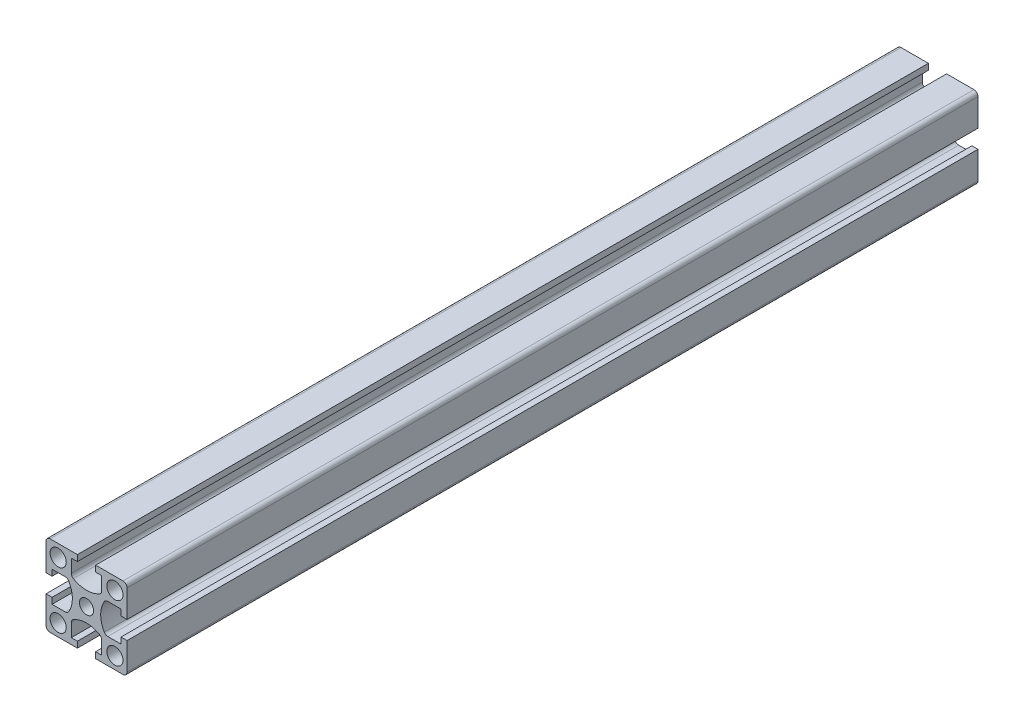
SolidWorks part; units mm, degrees
ref_plane "Front Plane" through (0, 0, 0) normal (0, 0, 1) x (1, 0, 0)
ref_plane "Top Plane" through (0, 0, 0) normal (0, 1, 0) x (1, 0, 0)
ref_plane "Right Plane" through (0, 0, 0) normal (1, 0, 0) x (0, 0, -1)
sketch "Sketch1" plane through (0, 0, 0) normal (0, 0, 1) x (1, 0, 0)
  line L64 (-20, 18) -> (-20, 4.5)
  line L65 (-20, 4.5) -> (-17, 4.5)
  line L66 (-17, 4.5) -> (-17, 7.5)
  line L67 (-17, 7.5) -> (-10.4737, 7.5)
  line L68 (-10.4737, -7.5) -> (-17, -7.5)
  line L69 (-17, -7.5) -> (-17, -4.5)
  line L70 (-17, -4.5) -> (-20, -4.5)
  line L71 (-20, -4.5) -> (-20, -18)
  line L72 (-18, -20) -> (-4.5, -20)
  line L73 (-4.5, -20) -> (-4.5, -17)
  line L74 (-4.5, -17) -> (-7.5, -17)
  line L75 (-7.5, -17) -> (-7.5, -10.4737)
  line L76 (7.5, -10.4737) -> (7.5, -17)
  line L77 (7.5, -17) -> (4.5, -17)
  line L78 (4.5, -17) -> (4.5, -20)
  line L79 (4.5, -20) -> (18, -20)
  line L80 (20, -18) -> (20, -4.5)
  line L81 (20, -4.5) -> (17, -4.5)
  line L82 (17, -4.5) -> (17, -7.5)
  line L83 (17, -7.5) -> (10.4737, -7.5)
  line L84 (10.4737, 7.5) -> (17, 7.5)
  line L85 (17, 7.5) -> (17, 4.5)
  line L86 (17, 4.5) -> (20, 4.5)
  line L87 (20, 4.5) -> (20, 18)
  line L88 (18, 20) -> (4.5, 20)
  line L89 (4.5, 20) -> (4.5, 17)
  line L90 (4.5, 17) -> (7.5, 17)
  line L91 (7.5, 17) -> (7.5, 10.4737)
  line L92 (-7.5, 10.4737) -> (-7.5, 17)
  line L93 (-7.5, 17) -> (-4.5, 17)
  line L94 (-4.5, 17) -> (-4.5, 20)
  line L95 (-4.5, 20) -> (-18, 20)
  circle A5 centre (-14, -14) radius 4
  circle A6 centre (14, -14) radius 4
  circle A7 centre (14, 14) radius 4
  circle A8 centre (0, 0) radius 3.5
  circle A9 centre (-14, 14) radius 4
  arc A32 (-18, 20) -> (-20, 18) centre (-18, 18) ccw
  arc A33 (-8.7417, 6.5) -> (-10.4737, 7.5) centre (-10.4737, 5.5) ccw
  arc A34 (-8.7417, -6.5) -> (-8.7417, 6.5) centre (-20, 0) ccw
  arc A35 (-10.4737, -7.5) -> (-8.7417, -6.5) centre (-10.4737, -5.5) ccw
  arc A36 (-20, -18) -> (-18, -20) centre (-18, -18) ccw
  arc A37 (-6.5, -8.7417) -> (-7.5, -10.4737) centre (-5.5, -10.4737) ccw
  arc A38 (6.5, -8.7417) -> (-6.5, -8.7417) centre (0, -20) ccw
  arc A39 (7.5, -10.4737) -> (6.5, -8.7417) centre (5.5, -10.4737) ccw
  arc A40 (18, -20) -> (20, -18) centre (18, -18) ccw
  arc A41 (8.7417, -6.5) -> (10.4737, -7.5) centre (10.4737, -5.5) ccw
  arc A42 (8.7417, 6.5) -> (8.7417, -6.5) centre (20, 0) ccw
  arc A43 (10.4737, 7.5) -> (8.7417, 6.5) centre (10.4737, 5.5) ccw
  arc A44 (20, 18) -> (18, 20) centre (18, 18) ccw
  arc A45 (6.5, 8.7417) -> (7.5, 10.4737) centre (5.5, 10.4737) ccw
  arc A46 (-6.5, 8.7417) -> (6.5, 8.7417) centre (0, 20) ccw
  arc A47 (-7.5, 10.4737) -> (-6.5, 8.7417) centre (-5.5, 10.4737) ccw
extrude "Boss-Extrude1" add sketch "Sketch1" along normal blind 420
